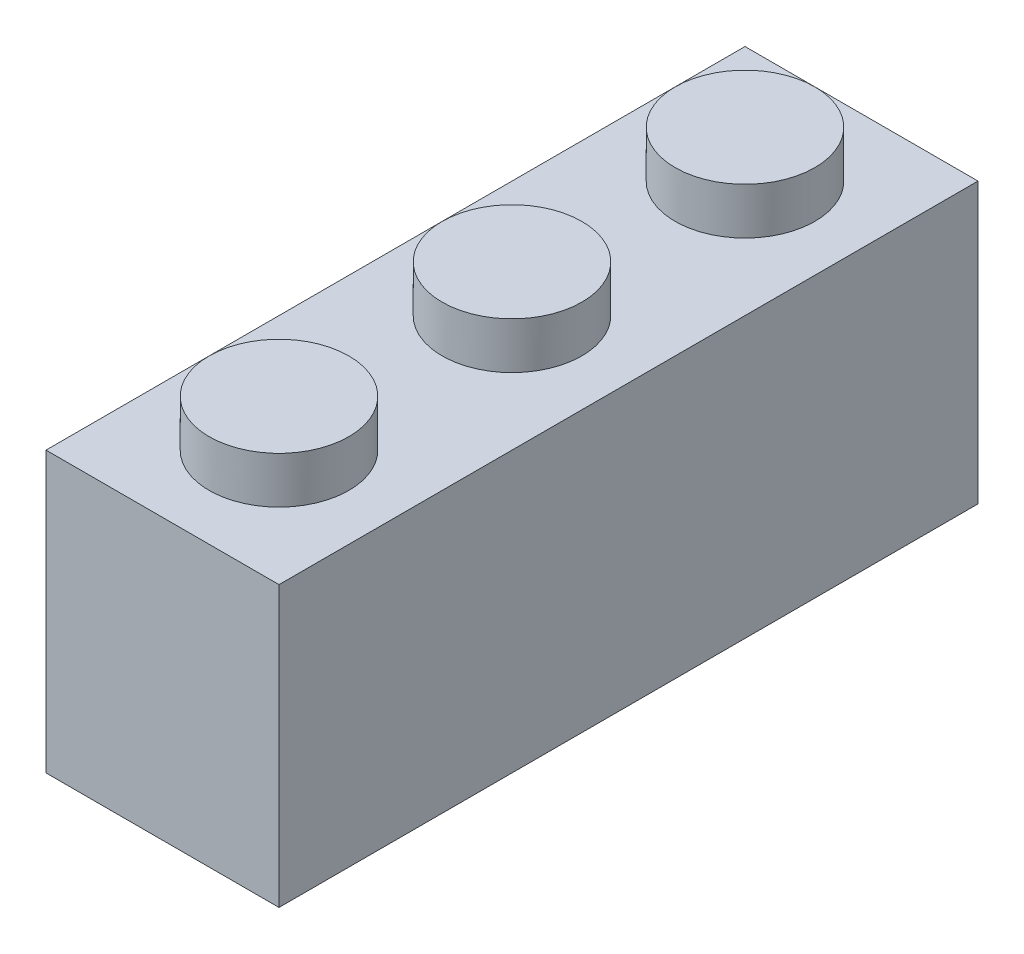
SolidWorks part; units mm, degrees
ref_plane "Front Plane" through (0, 0, 0) normal (0, 0, 1) x (1, 0, 0)
ref_plane "Top Plane" through (0, 0, 0) normal (0, 1, 0) x (1, 0, 0)
ref_plane "Right Plane" through (0, 0, 0) normal (1, 0, 0) x (0, 0, -1)
sketch "Sketch1" plane through (0, 0, 0) normal (0, 1, 0) x (1, 0, 0)
  line L1 (0, 0) -> (8, 0)
  line L2 (0, 0) -> (0, 24)
  line L3 (0, 24) -> (8, 24)
  line L4 (8, 0) -> (8, 24)
  dimension "D1" = 8
  dimension "D2" = 24
extrude "Boss-Extrude1" add sketch "Sketch1" along normal blind 9.6
sketch "Sketch2" plane through (0, 9.6, 0) normal (0, 1, 0) x (1, 0, 0)
  line L0 (4, 0) -> (4, 24) construction
  line L1 (0, 0) -> (8, 0) construction
  line L2 (8, 24) -> (0, 24) construction
  line L3 (8, 0) -> (8, 4) construction
  line L4 (8, 0) -> (8, 24) construction
  line L5 (8, 4) -> (4, 4) construction
  circle A0 centre (4, 4) radius 2.4
  dimension "D3" = 4.8
  dimension "D1" = 4
  dimension "D2" = 4
extrude "Boss-Extrude2" add sketch "Sketch2" along normal blind 1.6
pattern_linear "LPattern1" count 2 spacing 8 along (1, 0, 0) count 4 spacing 8 along (0, 0, -1) of "Boss-Extrude2"
shell "Shell1" thickness 1.6
